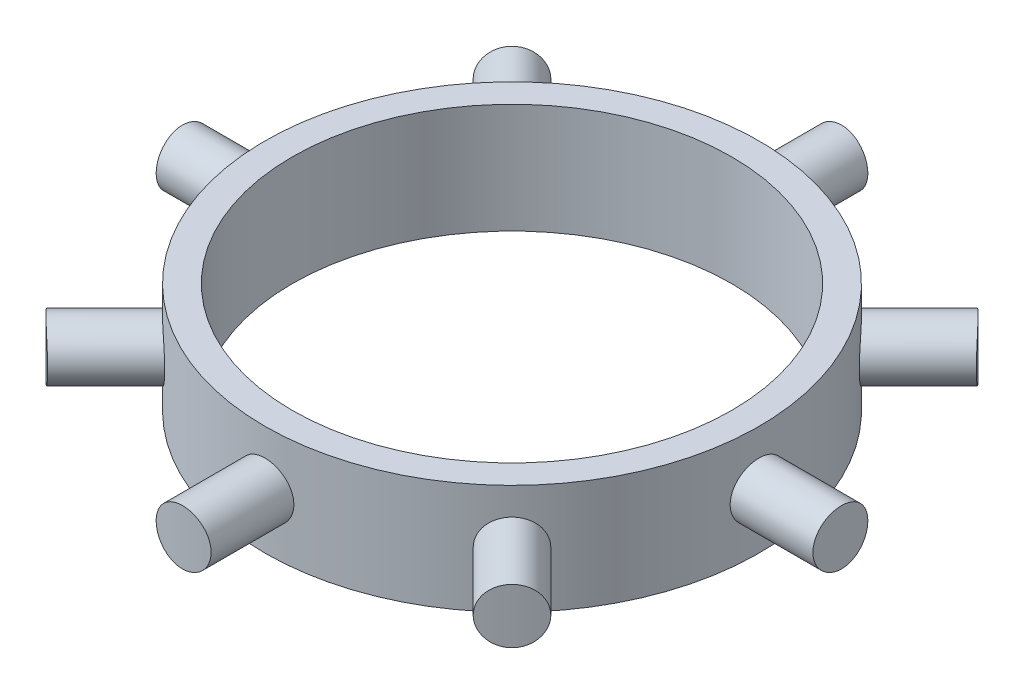
SolidWorks part; units mm, degrees
ref_plane "Front Plane" through (0, 0, 0) normal (0, 0, 1) x (1, 0, 0)
ref_plane "Top Plane" through (0, 0, 0) normal (0, 1, 0) x (1, 0, 0)
ref_plane "Right Plane" through (0, 0, 0) normal (1, 0, 0) x (0, 0, -1)
sketch "Sketch1" plane through (0, 0, 0) normal (0, 1, 0) x (1, 0, 0)
  circle A0 centre (0, 0) radius 20
  circle A1 centre (0, 0) radius 22.5
  dimension "D1" = 40
  dimension "D2" = 45
extrude "Boss-Extrude1" add sketch "Sketch1" along normal mid plane 10
sketch "Sketch4" plane through (0, 0, 0) normal (1, 0, 0) x (0, 0, -1)
  circle A0 centre (0, 0) radius 2.5
  dimension "D1" = 5
extrude "Boss-Extrude3" add sketch "Sketch4" along normal blind 30
sketch "Sketch5" plane through (0, -5, 0) normal (0, -1, 0) x (1, 0, 0)
  circle A0 centre (0, 0) radius 20 construction
  circle A1 centre (0, 0) radius 20
extrude "Cut-Extrude1" cut sketch "Sketch5" against normal through all
pattern_circular "CirPattern1" count 8 over 360 about axis through (0, 0, 0) along (0, 1, 0) of "Boss-Extrude3"
sketch "Sketch6" plane through (0, -5, 0) normal (0, -1, 0) x (1, 0, 0)
  circle A0 centre (0, 0) radius 20 construction
  circle A1 centre (0, 0) radius 20
extrude "Cut-Extrude2" cut sketch "Sketch6" against normal through all
sketch "Sketch7" plane through (0, 5, 0) normal (0, 1, 0) x (1, 0, 0)
  circle A0 centre (0, 0) radius 30
  dimension "D1" = 60
extrude "Cut-Extrude4" cut sketch "Sketch7" against normal through all flip side to cut
